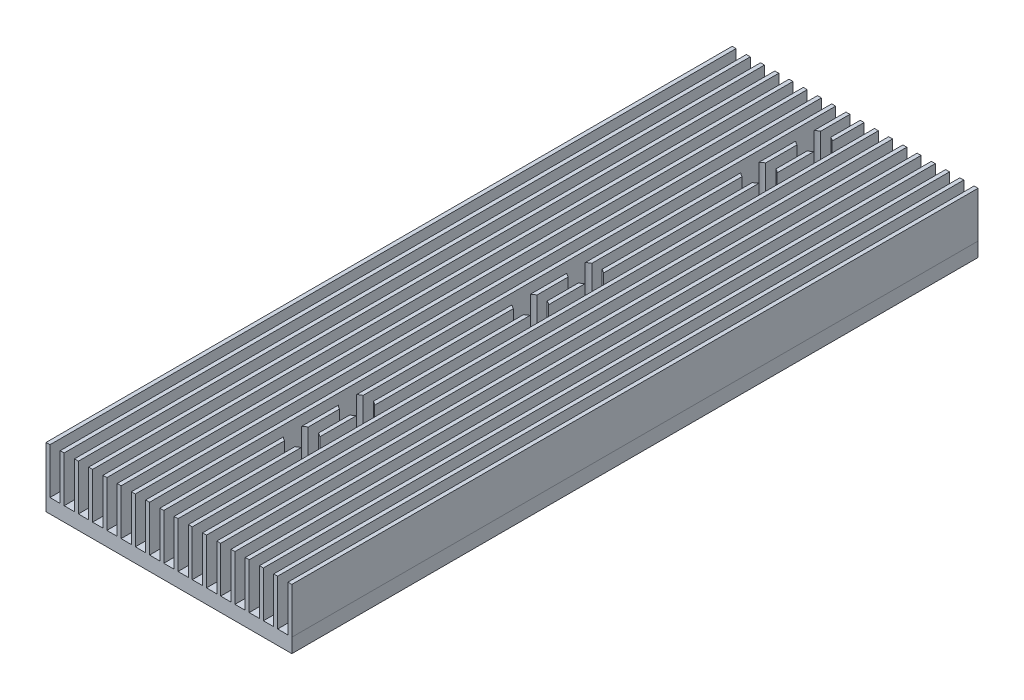
SolidWorks part; units mm, degrees
material "6061 Alloy"
ref_plane "Front Plane" through (0, 0, 0) normal (0, 0, 1) x (1, 0, 0)
ref_plane "Top Plane" through (0, 0, 0) normal (0, 1, 0) x (1, 0, 0)
ref_plane "Right Plane" through (0, 0, 0) normal (1, 0, 0) x (0, 0, -1)
sketch "Sketch1" plane through (0, 0, 0) normal (0, 1, 0) x (1, 0, 0)
  line L1 (0, 0) -> (136.525, 0)
  line L2 (0, 0) -> (0, 381)
  line L3 (0, 381) -> (136.525, 381)
  line L4 (136.525, 0) -> (136.525, 381)
  dimension "D1" = 381
  dimension "D2" = 136.525
extrude "Extrude1" add sketch "Sketch1" along normal blind 7.9248
sketch "Sketch4" plane through (0, 7.9248, 0) normal (0, 1, 0) x (-1, 0, 0)
  line L0 (-136.525, -381) -> (0, -381) construction
  line L1 (0, -381) -> (-2.1844, -381)
  line L2 (0, -381) -> (0, 0)
  line L3 (0, 0) -> (-2.1844, 0)
  line L4 (-2.1844, -381) -> (-2.1844, 0)
  line L5 (0, 0) -> (-136.525, 0) construction
  line L7 (0, -381) -> (0, 0) construction
  dimension "D2" = 2.1844
extrude "Extrude2" add sketch "Sketch4" along normal blind 25.4
pattern_linear "LPattern1" count 18 spacing 7.9024 along (1, 0, 0) of "Extrude2"
sketch "Sketch5" plane through (0, 0, 0) normal (0, 1, 0) x (1, 0, 0)
  line L0 (68.2625, 0) -> (68.2625, 366.2352) construction
  circle A0 centre (68.2625, 215.9) radius 31.75
  circle A1 centre (68.2625, 88.9) radius 31.75
  circle A2 centre (68.2625, 342.9) radius 31.75
  dimension "D1" = 63.5
  dimension "D2" = 127
  dimension "D3" = 88.9
  dimension "D4" = 127
  dimension "D5" = 68.2625
sketch "Sketch6" plane through (0, 0, 0) normal (0, 1, 0) x (1, 0, 0)
  line L1 (68.2625, 0) -> (68.2625, 366.2352) construction
  circle A0 centre (68.2625, 358.14) radius 3.175
  circle A1 centre (68.2625, 327.66) radius 3.175
  circle A2 centre (68.2625, 200.66) radius 3.175
  circle A3 centre (68.2625, 231.14) radius 3.175
  circle A4 centre (68.2625, 73.66) radius 3.175
  circle A5 centre (68.2625, 104.14) radius 3.175
  dimension "D1" = 6.35
  dimension "D2" = 15.24
  dimension "D3" = 15.24
  dimension "D5" = 15.24
  dimension "D6" = 15.24
  dimension "D7" = 15.24
  dimension "D4" = 15.24
extrude "Cut-Extrude2" cut sketch "Sketch6" along normal blind 10.16
sketch "Sketch7" plane through (0, 7.9248, 0) normal (0, 1, 0) x (-1, 0, 0)
  circle A0 centre (-68.2625, -358.14) radius 7.1438
  circle A1 centre (-68.2625, -327.66) radius 7.1438
  circle A2 centre (-68.2625, -231.14) radius 7.1437
  circle A3 centre (-68.2625, -200.66) radius 7.1437
  circle A4 centre (-68.2625, -73.66) radius 7.1437
  circle A5 centre (-68.2625, -104.14) radius 7.1437
  dimension "D1" = 14.2875
extrude "Cut-Extrude3" cut sketch "Sketch7" along normal through all
